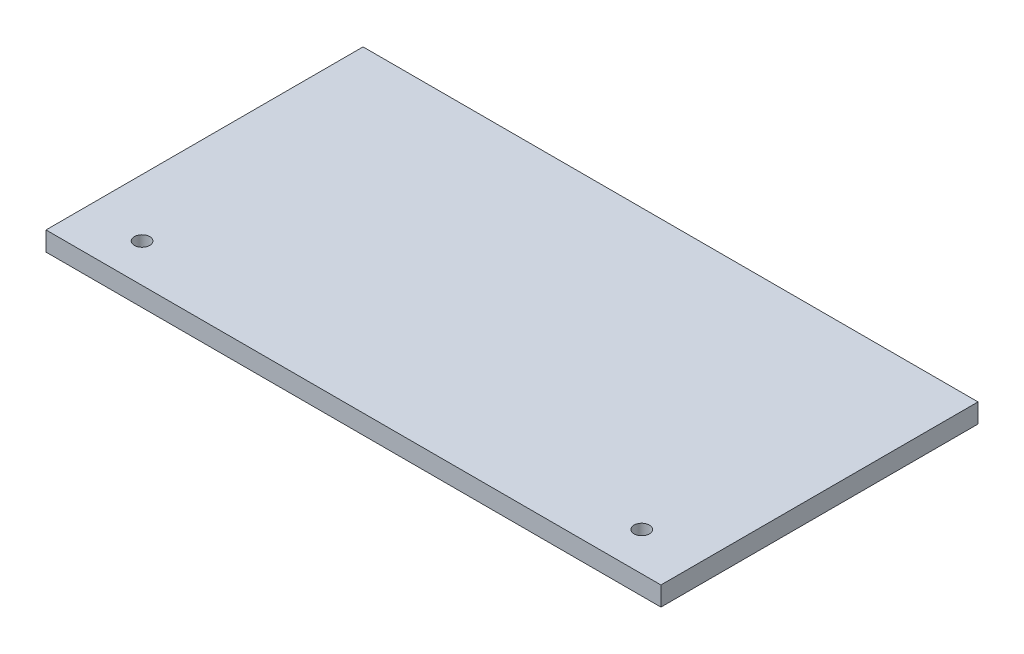
SolidWorks part; units mm, degrees
ref_plane "Front Plane" through (0, 0, 0) normal (0, 0, 1) x (1, 0, 0)
ref_plane "Top Plane" through (0, 0, 0) normal (0, 1, 0) x (1, 0, 0)
ref_plane "Right Plane" through (0, 0, 0) normal (1, 0, 0) x (0, 0, -1)
sketch "Sketch1" plane through (0, 0, 0) normal (0, 1, 0) x (1, 0, 0)
  line L1 (-64, -33) -> (64, -33)
  line L2 (-64, -33) -> (-64, 33)
  line L3 (-64, 33) -> (64, 33)
  line L4 (64, -33) -> (64, 33)
  circle A0 centre (-52, -25) radius 1.6
  circle A1 centre (52, -25) radius 1.6
extrude "Tray_Base_Extrude" add sketch "Sketch1" along normal blind 4
equation "\"ValveDiameter\" = 50mm"
equation "\"MotorGearTeeth\" = 40"
equation "\"OutputGearTeeth\" = 80"
equation "\"GearModule\" = 1.5mm"
equation "\"PressureAngle\" = 20deg"
equation "\"GearCenterDistance\" = 90mm"
equation "\"GearWidth\" = 18mm"
equation "\"OutputShaftDiameter\" = 20mm"
equation "\"BearingOD\" = 47mm"
equation "\"BearingWidth\" = 14mm"
equation "\"PlateThickness\" = 6mm"
equation "\"ValveRotation\" = 90deg"
